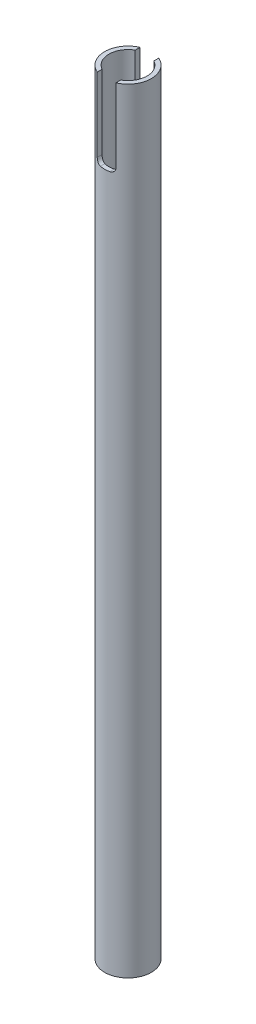
SolidWorks part; units mm, degrees
material "AISI 4130 Steel, normalized at 870C"
ref_plane "X-Y Datum" through (0, 0, 0) normal (0, 0, 1) x (1, 0, 0)
ref_plane "X-Z Datum" through (0, 0, 0) normal (0, 1, 0) x (1, 0, 0)
ref_plane "Y-Z Datum" through (0, 0, 0) normal (1, 0, 0) x (0, 0, -1)
sketch "Sketch1" plane through (0, 0, 0) normal (0, 1, 0) x (1, 0, 0)
  circle A0 centre (0, 0) radius 7.9375
  circle A1 centre (0, 0) radius 6.4643
  dimension "D1" = 1.4732
  dimension "D2" = 15.875
extrude "Boss-Extrude1" add sketch "Sketch1" along normal offset from surface (262.9524 mm away) 25.4 from surface at -124.4605
sketch "Sketch2" plane through (0, 0, 0) normal (0, 0, 1) x (1, 0, 0)
  line L0 (0, 111.8218) -> (0, 138.4918) construction
  line L1 (-3.175, 138.4918) -> (3.175, 138.4918)
  line L2 (-3.175, 138.4918) -> (-3.175, 113.4093)
  line L3 (-1.5875, 111.8218) -> (1.5875, 111.8218)
  line L4 (3.175, 138.4918) -> (3.175, 113.4093)
  line L5 (6.4643, 138.4918) -> (-6.4643, 138.4918) construction
  line L7 (-3.175, 113.0918) -> (3.175, 113.0918) construction
  line L10 (3.175, 116.2668) -> (3.175, 146.4293) construction
  arc A0 (-3.175, 113.4093) -> (-1.5875, 111.8218) centre (-1.5875, 113.4093) ccw
  arc A1 (1.5875, 111.8218) -> (3.175, 113.4093) centre (1.5875, 113.4093) ccw
  dimension "D2" = 1.5875
  dimension "D1" = 1.27
extrude "Cut-Extrude1" cut sketch "Sketch2" against normal through all both and the other way through all
